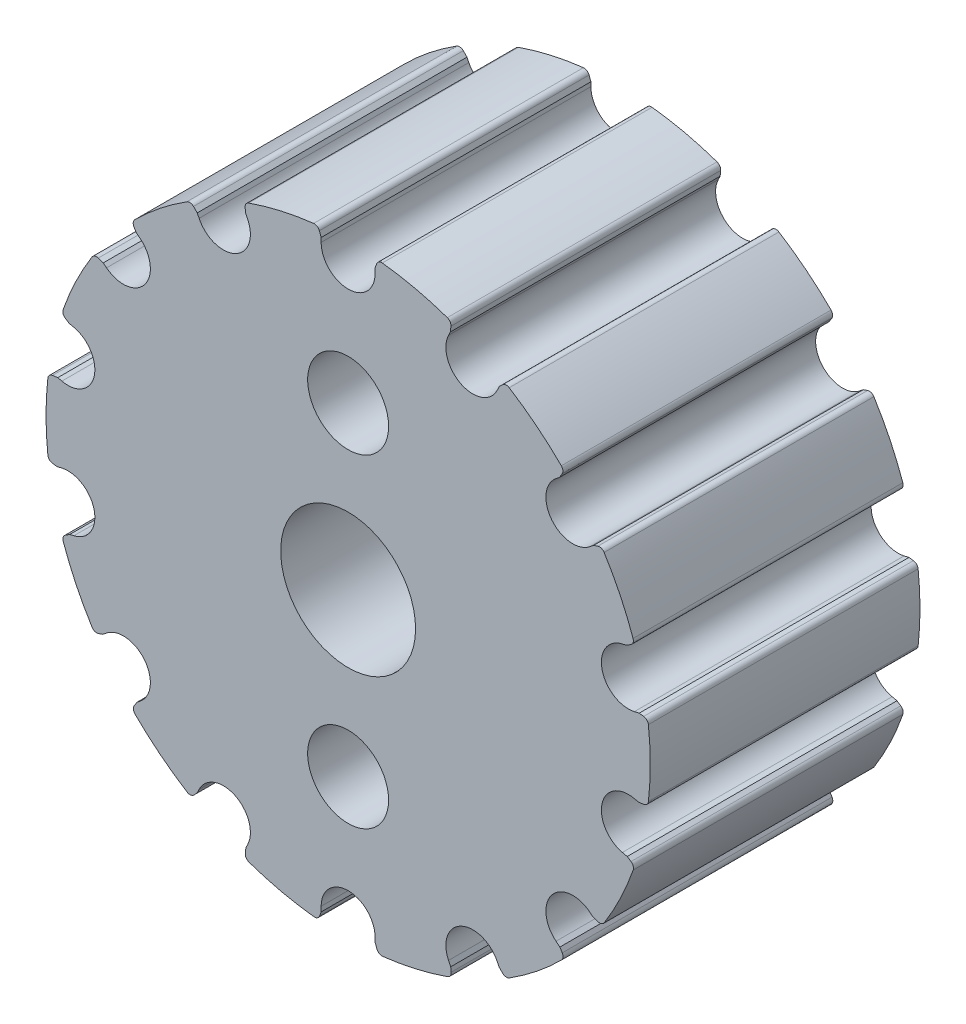
SolidWorks part; units mm, degrees
ref_plane "Спереди" through (0, 0, 0) normal (0, 0, 1) x (1, 0, 0)
ref_plane "Сверху" through (0, 0, 0) normal (0, 1, 0) x (1, 0, 0)
ref_plane "Справа" through (0, 0, 0) normal (1, 0, 0) x (0, 0, -1)
sketch "Эскиз1" plane through (0, 0, 0) normal (0, 0, 1) x (1, 0, 0)
  line L0 (0, 0) -> (0, 13.132) construction
  line L1 (-0.6859, 9.95) -> (0, 9.95)
  line L2 (0, 9.95) -> (0.676, 9.95)
  line L3 (-0.6859, 9.95) -> (-1.1204, 11.1438)
  line L4 (0, 11.2) -> (1.7516, 11.2) construction
  line L5 (3.6991, 9.2623) -> (3.8256, 10.5264)
  line L6 (1.1109, 11.1448) -> (0.676, 9.95)
  line L7 (3.6991, 9.2623) -> (4.3171, 8.9646)
  line L8 (4.3171, 8.9646) -> (4.9262, 8.6713)
  line L9 (5.8364, 9.5591) -> (4.9262, 8.6713)
  line L10 (7.3516, 6.74) -> (8.014, 7.8241)
  line L11 (7.3516, 6.74) -> (7.7792, 6.2037)
  line L12 (7.7792, 6.2037) -> (8.2007, 5.6752)
  line L13 (9.4059, 6.0801) -> (8.2007, 5.6752)
  line L14 (9.5479, 2.8828) -> (10.6151, 3.5721)
  line L15 (9.5479, 2.8828) -> (9.7005, 2.2141)
  line L16 (9.7005, 2.2141) -> (9.851, 1.555)
  line L17 (11.1125, 1.3969) -> (9.851, 1.555)
  line L18 (9.8532, -1.5453) -> (11.1137, -1.3874)
  line L19 (9.8532, -1.5453) -> (9.7005, -2.2141)
  line L20 (9.7005, -2.2141) -> (9.5501, -2.8731)
  line L21 (10.6182, -3.563) -> (9.5501, -2.8731)
  line L22 (8.2069, -5.6674) -> (9.4112, -6.0721)
  line L23 (8.2069, -5.6674) -> (7.7792, -6.2037)
  line L24 (7.7792, -6.2037) -> (7.3577, -6.7322)
  line L25 (8.0207, -7.8172) -> (7.3577, -6.7322)
  line L26 (4.9351, -8.667) -> (5.8446, -9.5541)
  line L27 (4.9351, -8.667) -> (4.3171, -8.9646)
  line L28 (4.3171, -8.9646) -> (3.7081, -9.2579)
  line L29 (3.8347, -10.5231) -> (3.7081, -9.2579)
  line L30 (0.6859, -9.95) -> (1.1204, -11.1438)
  line L31 (0.6859, -9.95) -> (0, -9.95)
  line L32 (0, -9.95) -> (-0.676, -9.95)
  line L33 (-1.1109, -11.1448) -> (-0.676, -9.95)
  line L34 (-3.6991, -9.2623) -> (-3.8256, -10.5264)
  line L35 (-3.6991, -9.2623) -> (-4.3171, -8.9646)
  line L36 (-4.3171, -8.9646) -> (-4.9262, -8.6713)
  line L37 (-5.8364, -9.5591) -> (-4.9262, -8.6713)
  line L38 (-7.3516, -6.74) -> (-8.014, -7.8241)
  line L39 (-7.3516, -6.74) -> (-7.7792, -6.2037)
  line L40 (-7.7792, -6.2037) -> (-8.2007, -5.6752)
  line L41 (-9.4059, -6.0801) -> (-8.2007, -5.6752)
  line L42 (-9.5479, -2.8828) -> (-10.6151, -3.5721)
  line L43 (-9.5479, -2.8828) -> (-9.7005, -2.2141)
  line L44 (-9.7005, -2.2141) -> (-9.851, -1.555)
  line L45 (-11.1125, -1.3969) -> (-9.851, -1.555)
  line L46 (-9.8532, 1.5453) -> (-11.1137, 1.3874)
  line L47 (-9.8532, 1.5453) -> (-9.7005, 2.2141)
  line L48 (-9.7005, 2.2141) -> (-9.5501, 2.8731)
  line L49 (-10.6182, 3.563) -> (-9.5501, 2.8731)
  line L50 (-8.2069, 5.6674) -> (-9.4112, 6.0721)
  line L51 (-8.2069, 5.6674) -> (-7.7792, 6.2037)
  line L52 (-7.7792, 6.2037) -> (-7.3577, 6.7322)
  line L53 (-8.0207, 7.8172) -> (-7.3577, 6.7322)
  line L54 (-4.9351, 8.667) -> (-5.8446, 9.5541)
  line L55 (-4.9351, 8.667) -> (-4.3171, 8.9646)
  line L56 (-4.3171, 8.9646) -> (-3.7081, 9.2579)
  line L57 (-3.8347, 10.5231) -> (-3.7081, 9.2579)
  line L114 (0, 9.95) -> (0, 22.3219) construction
  arc A0 (3.8256, 10.5264) -> (1.1109, 11.1448) centre (0, 0) ccw
  circle A1 centre (0, 0) radius 2.5
  circle A2 centre (0, 6) radius 1.5
  circle A3 centre (0, -6) radius 1.5
  arc A4 (8.014, 7.8241) -> (5.8364, 9.5591) centre (0, 0) ccw
  arc A5 (10.6151, 3.5721) -> (9.4059, 6.0801) centre (0, 0) ccw
  arc A6 (11.1137, -1.3874) -> (11.1125, 1.3969) centre (0, 0) ccw
  arc A7 (9.4112, -6.0721) -> (10.6182, -3.563) centre (0, 0) ccw
  arc A8 (5.8446, -9.5541) -> (8.0207, -7.8172) centre (0, 0) ccw
  arc A9 (1.1204, -11.1438) -> (3.8347, -10.5231) centre (0, 0) ccw
  arc A10 (-3.8256, -10.5264) -> (-1.1109, -11.1448) centre (0, 0) ccw
  arc A11 (-8.014, -7.8241) -> (-5.8364, -9.5591) centre (0, 0) ccw
  arc A12 (-10.6151, -3.5721) -> (-9.4059, -6.0801) centre (0, 0) ccw
  arc A13 (-11.1137, 1.3874) -> (-11.1125, -1.3969) centre (0, 0) ccw
  arc A14 (-9.4112, 6.0721) -> (-10.6182, 3.563) centre (0, 0) ccw
  arc A15 (-5.8446, 9.5541) -> (-8.0207, 7.8172) centre (0, 0) ccw
  arc A16 (-1.1204, 11.1438) -> (-3.8347, 10.5231) centre (0, 0) ccw
  dimension "D4" = 40
  dimension "D6" = 1.25
  dimension "D7" = 22.4
  dimension "D8" = 6
  dimension "D3" = 0.676
  dimension "D5" = 110
extrude "Вытянуть1" add sketch "Эскиз1" along normal blind 10
fillet "Скругление1" radius 0.2 55 edges at (-9.5479, -2.8828, 5) (-10.6151, -3.5721, 5) (-7.3516, -6.74, 5) (-8.014, -7.8241, 5) (-11.1125, -1.3969, 5) (-9.851, -1.555, 5) (-9.4059, -6.0801, 5) (-8.2007, -5.6752, 5) (-5.8364, -9.5591, 5) (-4.9262, -8.6713, 5) (-3.6991, -9.2623, 5) (-3.8256, -10.5264, 5) (1.1204, -11.1438, 5) (0.6859, -9.95, 5) (-1.1109, -11.1448, 5) (-0.676, -9.95, 5) (4.9351, -8.667, 5) (5.8446, -9.5541, 5) (3.8347, -10.5231, 5) (3.7081, -9.2579, 5) (8.0207, -7.8172, 5) (7.3577, -6.7322, 5) (8.2069, -5.6674, 5) (9.4112, -6.0721, 5) (9.8532, -1.5453, 5) (11.1137, -1.3874, 5) (10.6182, -3.563, 5) (9.5501, -2.8731, 5) (11.1125, 1.3969, 5) (9.851, 1.555, 5) (9.5479, 2.8828, 5) (10.6151, 3.5721, 5) (8.014, 7.8241, 5) (7.3516, 6.74, 5) (9.4059, 6.0801, 5) (8.2007, 5.6752, 5) (3.6991, 9.2623, 5) (3.8256, 10.5264, 5) (5.8364, 9.5591, 5) (4.9262, 8.6713, 5) (-0.6859, 9.95, 5) (-1.1204, 11.1438, 5) (1.1109, 11.1448, 5) (0.676, 9.95, 5) (-4.9351, 8.667, 5) (-5.8446, 9.5541, 5) (-3.8347, 10.5231, 5) (-3.7081, 9.2579, 5) (-8.0207, 7.8172, 5) (-7.3577, 6.7322, 5) (-11.1137, 1.3874, 5) (-9.8532, 1.5453, 5) (-10.6182, 3.563, 5) (-9.4112, 6.0721, 5) (-8.2069, 5.6674, 5)
sketch "Эскиз2" plane through (0, 0, 10) normal (0, 0, 1) x (1, 0, 0)
  line L0 (0, 0) -> (0, 13.8774) construction
  line L1 (4.7401, 12.1477) -> (6.542, 11.2799)
  line L2 (-1, 13.0013) -> (1, 13.0013)
  line L3 (-1, 13.0013) -> (-1, 10.6564)
  line L4 (4.7401, 12.1477) -> (3.7227, 10.035)
  line L5 (1, 13.0013) -> (1, 10.6564)
  line L6 (6.542, 11.2799) -> (5.5246, 9.1672)
  line L7 (9.5414, 8.888) -> (10.7884, 7.3244)
  line L8 (9.5414, 8.888) -> (7.708, 7.426)
  line L9 (10.7884, 7.3244) -> (8.955, 5.8623)
  line L10 (12.4529, 3.868) -> (12.8979, 1.9181)
  line L11 (12.4529, 3.868) -> (10.1667, 3.3462)
  line L12 (12.8979, 1.9181) -> (10.6117, 1.3963)
  line L13 (12.8979, -1.9181) -> (12.4529, -3.868)
  line L14 (12.8979, -1.9181) -> (10.6117, -1.3963)
  line L15 (12.4529, -3.868) -> (10.1667, -3.3462)
  line L16 (10.7884, -7.3244) -> (9.5414, -8.888)
  line L17 (10.7884, -7.3244) -> (8.955, -5.8623)
  line L18 (9.5414, -8.888) -> (7.708, -7.426)
  line L19 (6.542, -11.2799) -> (4.7401, -12.1477)
  line L20 (6.542, -11.2799) -> (5.5246, -9.1672)
  line L21 (4.7401, -12.1477) -> (3.7227, -10.035)
  line L22 (1, -13.0013) -> (-1, -13.0013)
  line L23 (1, -13.0013) -> (1, -10.6564)
  line L24 (-1, -13.0013) -> (-1, -10.6564)
  line L25 (-4.7401, -12.1477) -> (-6.542, -11.2799)
  line L26 (-4.7401, -12.1477) -> (-3.7227, -10.035)
  line L27 (-6.542, -11.2799) -> (-5.5246, -9.1672)
  line L28 (-9.5414, -8.888) -> (-10.7884, -7.3244)
  line L29 (-9.5414, -8.888) -> (-7.708, -7.426)
  line L30 (-10.7884, -7.3244) -> (-8.955, -5.8623)
  line L31 (-12.4529, -3.868) -> (-12.8979, -1.9181)
  line L32 (-12.4529, -3.868) -> (-10.1667, -3.3462)
  line L33 (-12.8979, -1.9181) -> (-10.6117, -1.3963)
  line L34 (-12.8979, 1.9181) -> (-12.4529, 3.868)
  line L35 (-12.8979, 1.9181) -> (-10.6117, 1.3963)
  line L36 (-12.4529, 3.868) -> (-10.1667, 3.3462)
  line L37 (-10.7884, 7.3244) -> (-9.5414, 8.888)
  line L38 (-10.7884, 7.3244) -> (-8.955, 5.8623)
  line L39 (-9.5414, 8.888) -> (-7.708, 7.426)
  line L40 (-6.542, 11.2799) -> (-4.7401, 12.1477)
  line L41 (-6.542, 11.2799) -> (-5.5246, 9.1672)
  line L42 (-4.7401, 12.1477) -> (-3.7227, 10.035)
  arc A0 (-1, 10.6564) -> (1, 10.6564) centre (0, 10.6564) ccw
  arc A1 (3.7227, 10.035) -> (5.5246, 9.1672) centre (4.6236, 9.6011) ccw
  arc A2 (7.708, 7.426) -> (8.955, 5.8623) centre (8.3315, 6.6442) ccw
  arc A3 (10.1667, 3.3462) -> (10.6117, 1.3963) centre (10.3892, 2.3713) ccw
  arc A4 (10.6117, -1.3963) -> (10.1667, -3.3462) centre (10.3892, -2.3713) ccw
  arc A5 (8.955, -5.8623) -> (7.708, -7.426) centre (8.3315, -6.6442) ccw
  arc A6 (5.5246, -9.1672) -> (3.7227, -10.035) centre (4.6236, -9.6011) ccw
  arc A7 (1, -10.6564) -> (-1, -10.6564) centre (0, -10.6564) ccw
  arc A8 (-3.7227, -10.035) -> (-5.5246, -9.1672) centre (-4.6236, -9.6011) ccw
  arc A9 (-7.708, -7.426) -> (-8.955, -5.8623) centre (-8.3315, -6.6442) ccw
  arc A10 (-10.1667, -3.3462) -> (-10.6117, -1.3963) centre (-10.3892, -2.3713) ccw
  arc A11 (-10.6117, 1.3963) -> (-10.1667, 3.3462) centre (-10.3892, 2.3713) ccw
  arc A12 (-8.955, 5.8623) -> (-7.708, 7.426) centre (-8.3315, 6.6442) ccw
  arc A13 (-5.5246, 9.1672) -> (-3.7227, 10.035) centre (-4.6236, 9.6011) ccw
  dimension "D1" = 1
  dimension "D2" = 1
extrude "Вырез-Вытянуть1" cut sketch "Эскиз2" against normal blind 10
